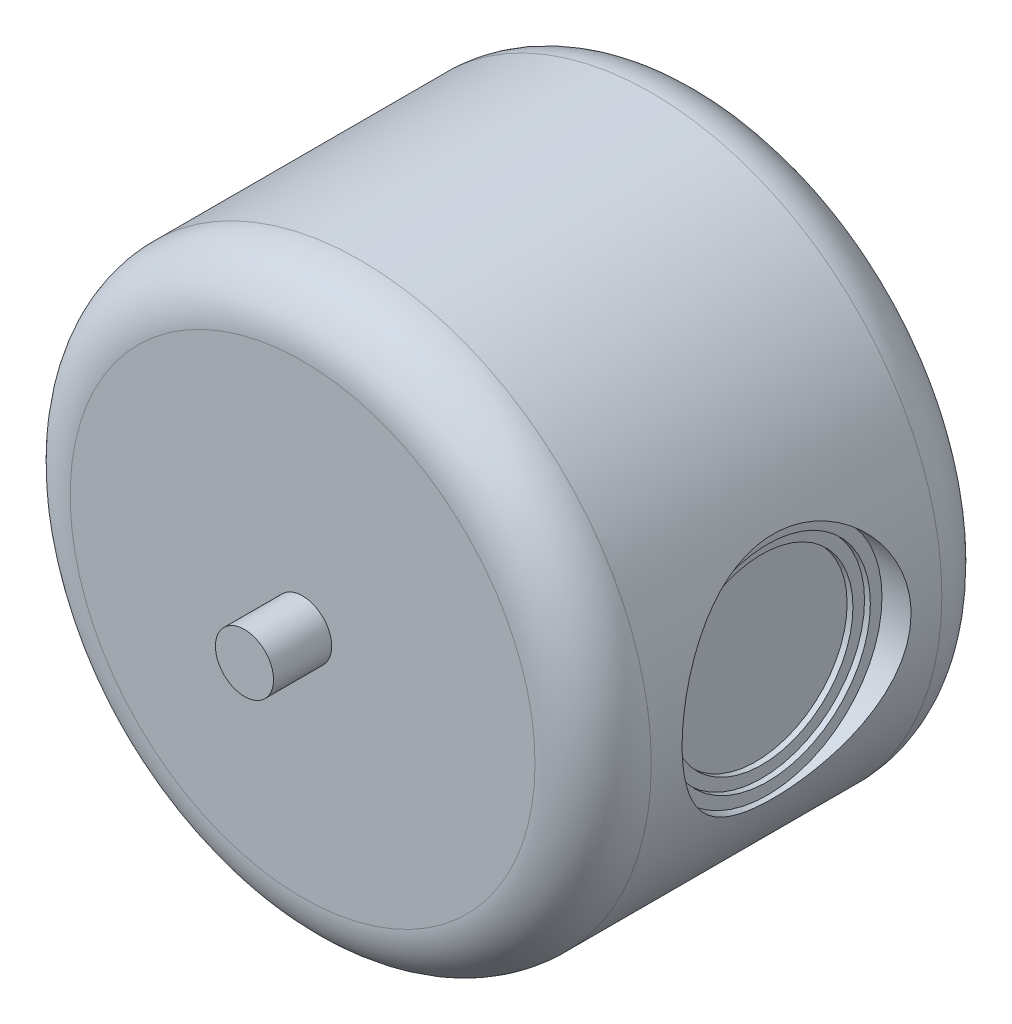
SolidWorks part; units mm, degrees
ref_plane "Front Plane" through (0, 0, 0) normal (0, 0, 1) x (1, 0, 0)
ref_plane "Top Plane" through (0, 0, 0) normal (0, 1, 0) x (1, 0, 0)
ref_plane "Right Plane" through (0, 0, 0) normal (1, 0, 0) x (0, 0, -1)
sketch "Sketch1" plane through (0, 0, 0) normal (0, 0, 1) x (1, 0, 0)
  circle A0 centre (0, 0) radius 50
  dimension "D1" = 100
extrude "Boss-Extrude1" add sketch "Sketch1" along normal mid plane 70
sketch "Sketch2" plane through (0, 0, 0) normal (0, 0, 1) x (1, 0, 0)
  circle A0 centre (0, 0) radius 5
  dimension "D1" = 10
extrude "Boss-Extrude2" add sketch "Sketch2" along normal mid plane 90
fillet "Fillet1" radius 10 2 edges at (50, 0, -35) (50, 0, 35)
ref_plane "Plane1" through (50, 0, 0) normal (1, 0, 0) x (0, 0, -1)
sketch "Sketch3" plane through (50, 0, 0) normal (1, 0, 0) x (0, 0, -1)
  circle A0 centre (0, 0) radius 19.6987
extrude "Cut-Extrude1" cut sketch "Sketch3" against normal blind 5
sketch "Sketch4" plane through (45, 0, 0) normal (1, 0, 0) x (0, 0, -1)
  circle A2 centre (0, 0) radius 17.6987
  circle A3 centre (0, 0) radius 17.6987
  dimension "D1" = 2
extrude "Cut-Extrude2" cut sketch "Sketch4" against normal blind 1
sketch "Sketch5" plane through (44, 0, 0) normal (1, 0, 0) x (0, 0, -1)
  circle A2 centre (0, 0) radius 15.6987
  circle A3 centre (0, 0) radius 15.6987
  dimension "D1" = 2
extrude "Cut-Extrude3" cut sketch "Sketch5" against normal blind 1
